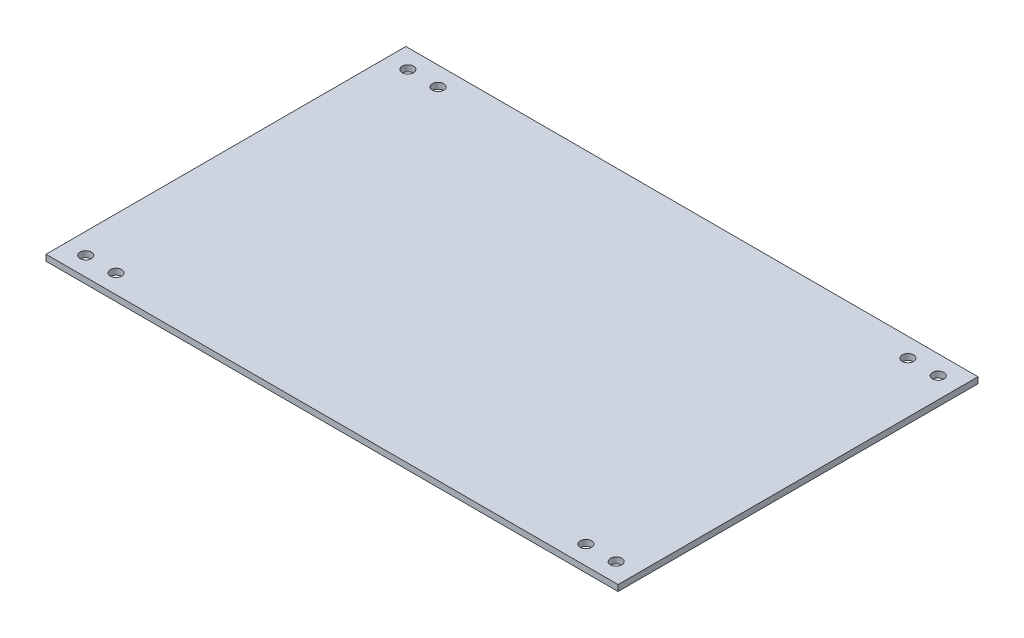
SolidWorks part; units mm, degrees
ref_plane "前视基准面" through (0, 0, 0) normal (0, 0, 1) x (1, 0, 0)
ref_plane "上视基准面" through (0, 0, 0) normal (0, 1, 0) x (1, 0, 0)
ref_plane "右视基准面" through (0, 0, 0) normal (1, 0, 0) x (0, 0, -1)
other "Configuration Table"
sketch "草图1" plane through (0, 0, 0) normal (0, 1, 0) x (1, 0, 0)
  line L1 (0, 0) -> (151, 0)
  line L2 (0, 0) -> (0, 95)
  line L3 (0, 95) -> (151, 95)
  line L4 (151, 0) -> (151, 95)
  dimension "D1" = 151
  dimension "D2" = 95
extrude "凸台-拉伸1" add sketch "草图1" along normal blind 1.6
sketch "草图2" plane through (0, 1.6, 0) normal (0, 1, 0) x (1, 0, 0)
  line L0 (0, 47.5) -> (166.3822, 47.5) construction
  line L1 (0, 95) -> (0, 0) construction
  line L2 (75.5, 95) -> (75.5, -9.5195) construction
  line L3 (151, 95) -> (0, 95) construction
  circle A0 centre (5.5, 90) radius 1.5
  circle A1 centre (145.5, 90) radius 1.5
  circle A2 centre (145.5, 5) radius 1.5
  circle A3 centre (5.5, 5) radius 1.5
  circle A4 centre (13.5, 90) radius 1.5
  circle A5 centre (13.5, 5) radius 1.5
  circle A6 centre (137.5, 5) radius 1.5
  circle A7 centre (137.5, 90) radius 1.5
  point P18 (0, 0)
  point P19 (0, 0)
  dimension "D1" = 3
  dimension "D2" = 85
  dimension "D3" = 140
  dimension "D4" = 8
extrude "切除-拉伸1" cut sketch "草图2" against normal through all
